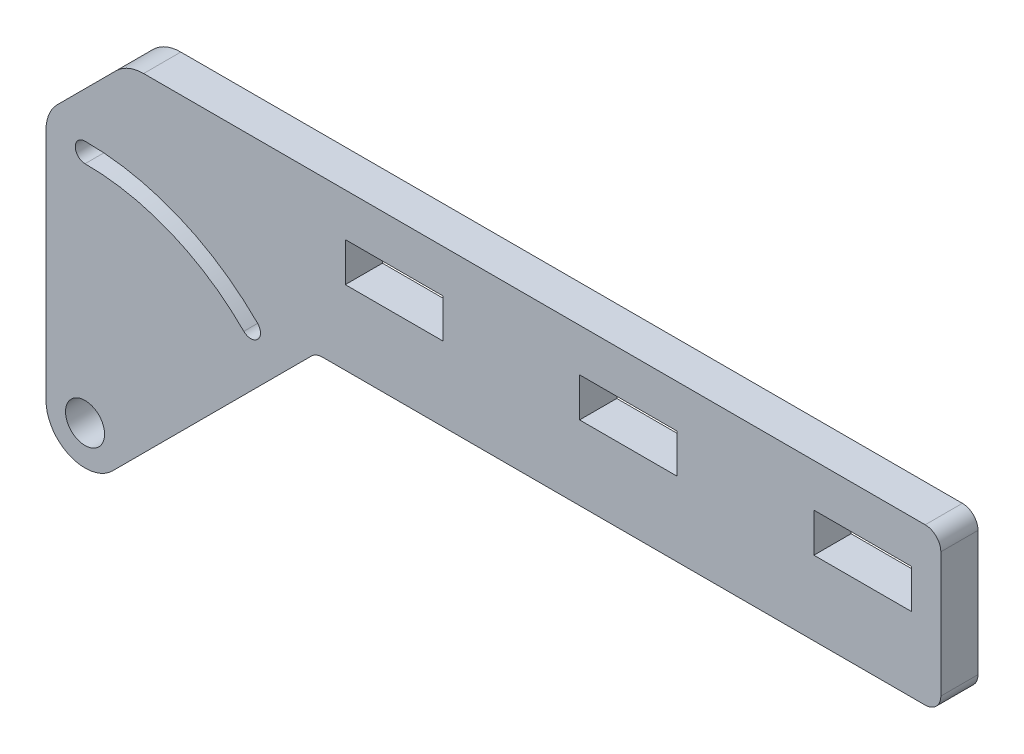
SolidWorks part; units mm, degrees
ref_plane "Front Plane" through (0, 0, 0) normal (0, 0, 1) x (1, 0, 0)
ref_plane "Top Plane" through (0, 0, 0) normal (0, 1, 0) x (1, 0, 0)
ref_plane "Right Plane" through (0, 0, 0) normal (1, 0, 0) x (0, 0, -1)
sketch "Sketch1" plane through (0, 0, 0) normal (0, 0, 1) x (1, 0, 0)
  line L0 (0, 0) -> (26.9408, 26.9408) construction
  line L1 (0, 0) -> (0, 38.1) construction
  line L2 (-6.35, 38.1) -> (-6.35, 0)
  line L3 (4.4901, -4.4901) -> (31.4309, 22.4506)
  line L4 (0, 0) -> (37.5553, 0) construction
  line L5 (37.5553, 0) -> (37.5553, 28.575) construction
  line L6 (36.8113, 27.8311) -> (31.4309, 22.4506)
  line L7 (38.6074, 28.575) -> (136.6153, 28.575)
  line L10 (139.1553, 31.115) -> (139.1553, 51.435)
  line L12 (136.6153, 53.975) -> (9.525, 53.975)
  line L13 (-4.4901, 42.5901) -> (5.0349, 52.1151)
  circle A0 centre (0, 0) radius 3.175
  arc A1 (-6.35, 0) -> (4.4901, -4.4901) centre (0, 0) ccw
  circle A2 centre (0, 0) radius 38.1 construction
  arc A3 (25.8182, 25.8182) -> (0, 36.5125) centre (0, 0) ccw
  arc A4 (28.0633, 28.0633) -> (0, 39.6875) centre (0, 0) ccw
  arc A5 (25.8182, 25.8182) -> (28.0633, 28.0633) centre (26.9408, 26.9408) ccw
  arc A6 (0, 39.6875) -> (0, 36.5125) centre (0, 38.1) ccw
  circle A9 centre (0, 0) radius 31.75 construction
  arc A10 (31.4309, 31.4309) -> (0, 44.45) centre (0, 0) ccw construction
  arc A12 (31.0411, 22.0921) -> (31.4309, 31.4309) centre (26.9408, 26.9408) ccw construction
  circle A13 centre (0, 38.1) radius 6.35 construction
  arc A14 (0, 44.45) -> (31.4309, 31.4309) centre (0, 0) ccw construction
  arc A15 (38.6074, 28.575) -> (36.8113, 27.8311) centre (38.6074, 26.035) ccw
  arc A16 (136.6153, 28.575) -> (139.1553, 31.115) centre (136.6153, 31.115) ccw
  arc A17 (-6.35, 38.1) -> (-4.4901, 42.5901) centre (0, 38.1) cw
  arc A18 (5.0349, 52.1151) -> (9.525, 53.975) centre (9.525, 47.625) cw
  arc A19 (139.1553, 51.435) -> (136.6153, 53.975) centre (136.6153, 51.435) ccw
  point P3 (8.9803, 0)
  point P12 (26.4872, 17.5069)
  point P29 (-6.35, 31.1085)
  dimension "D1" = 6.35
  dimension "D2" = 12.7
  dimension "D3" = 76.2
  dimension "D4" = 79.375
  dimension "D5" = 73.025
  dimension "D6" = 45
  dimension "D7" = 63.5
  dimension "D8" = 88.9
  dimension "D9" = 135
  dimension "D13" = 2.54
  dimension "D15" = 6.35
  dimension "D12" = 12.7
  dimension "D17" = 2.54
  dimension "D10" = 28.575
  dimension "D11" = 28.575
  dimension "D14" = 25.4
  dimension "D16" = 101.6
extrude "Boss-Extrude1" add sketch "Sketch1" along normal blind 6.0452
sketch "Sketch2" plane through (0, 0, 6.0452) normal (0, 0, 1) x (1, 0, 0)
  line L0 (38.6074, 28.575) -> (136.6153, 28.575) construction
  line L1 (118.5178, 46.99) -> (134.3928, 46.99)
  line L2 (118.5178, 46.99) -> (118.5178, 40.64)
  line L3 (118.5178, 40.64) -> (134.3928, 40.64)
  line L4 (134.3928, 46.99) -> (134.3928, 40.64)
  line L5 (139.1553, 31.115) -> (139.1553, 51.435) construction
  line L6 (80.4178, 46.99) -> (80.4178, 40.64)
  line L7 (80.4178, 46.99) -> (96.2928, 46.99)
  line L8 (96.2928, 46.99) -> (96.2928, 40.64)
  line L9 (80.4178, 40.64) -> (96.2928, 40.64)
  line L10 (42.3178, 46.99) -> (42.3178, 40.64)
  line L11 (42.3178, 46.99) -> (58.1928, 46.99)
  line L12 (58.1928, 46.99) -> (58.1928, 40.64)
  line L13 (42.3178, 40.64) -> (58.1928, 40.64)
  line L14 (118.5178, 46.99) -> (80.4178, 46.99) construction
  dimension "D1" = 15.875
  dimension "D2" = 6.35
  dimension "D3" = 12.065
  dimension "D4" = 4.7625
  dimension "D5" = 38.1
  dimension "D6" = 3
extrude "Cut-Extrude1" cut sketch "Sketch2" against normal blind 6.0452
